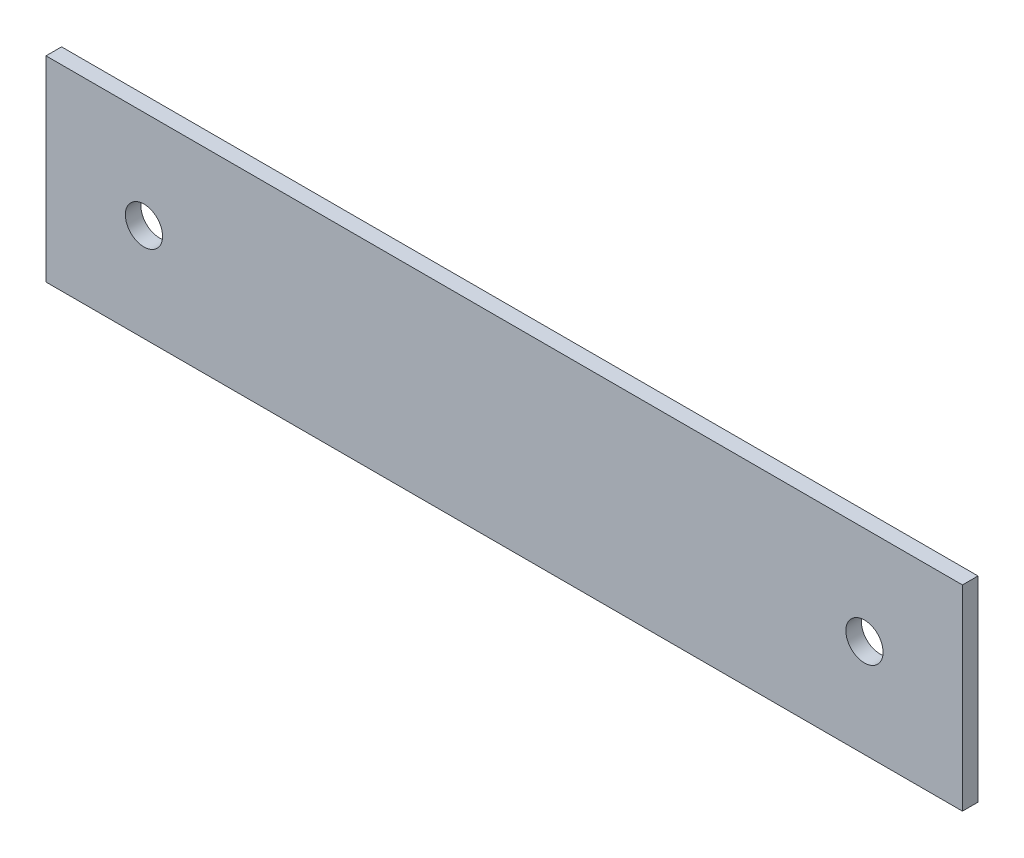
SolidWorks part; units mm, degrees
ref_plane "Front Plane" through (0, 0, 0) normal (0, 0, 1) x (1, 0, 0)
ref_plane "Top Plane" through (0, 0, 0) normal (0, 1, 0) x (1, 0, 0)
ref_plane "Right Plane" through (0, 0, 0) normal (1, 0, 0) x (0, 0, -1)
sketch "Sketch1" plane through (0, 0, 0) normal (0, 0, 1) x (1, 0, 0)
  line L1 (-46.77, 10) -> (46.77, 10)
  line L2 (-46.77, 10) -> (-46.77, -10)
  line L3 (-46.77, -10) -> (46.77, -10)
  line L4 (46.77, 10) -> (46.77, -10)
  line L5 (-46.77, 10) -> (46.77, -10) construction
  line L6 (-46.77, -10) -> (46.77, 10) construction
  point P0 (0, 0)
  dimension "D1" = 93.54
  dimension "D2" = 20
extrude "Boss-Extrude1" add sketch "Sketch1" along normal blind 1.5875
hole_wizard "#6 Clearance Hole1" positions "Sketch3" profile "Sketch2" hole size "#6" standard "ANSI Inch" end condition through all
sketch "Sketch3" plane through (0, 0, 1.5875) normal (0, 0, 1) x (1, 0, 0)
  line L0 (-46.77, 10) -> (-46.77, -10) construction
  line L1 (-46.77, -10) -> (46.77, -10) construction
  line L2 (46.77, -10) -> (46.77, 10) construction
  point P0 (-36.77, 0)
  point P2 (36.77, 0)
  dimension "D1" = 10
  dimension "D2" = 10
  dimension "D3" = 10
sketch "Sketch2" plane through (-36.77, 0, 1.5875) normal (1, 0, 0) x (0, -1, 0)
  line L0 (0, 0) -> (0, 1.5875)
  line L1 (0, 1.5875) -> (1.8986, 1.5875)
  line L2 (1.8986, 1.5875) -> (1.8986, 0)
  line L5 (1.8986, 0) -> (0, 0)
  line L11 (0, -6.35) -> (0, 107.95) construction
  dimension "Thru Hole Dia." = 3.7973
  dimension "Thru Hole Depth" = 1.5875
